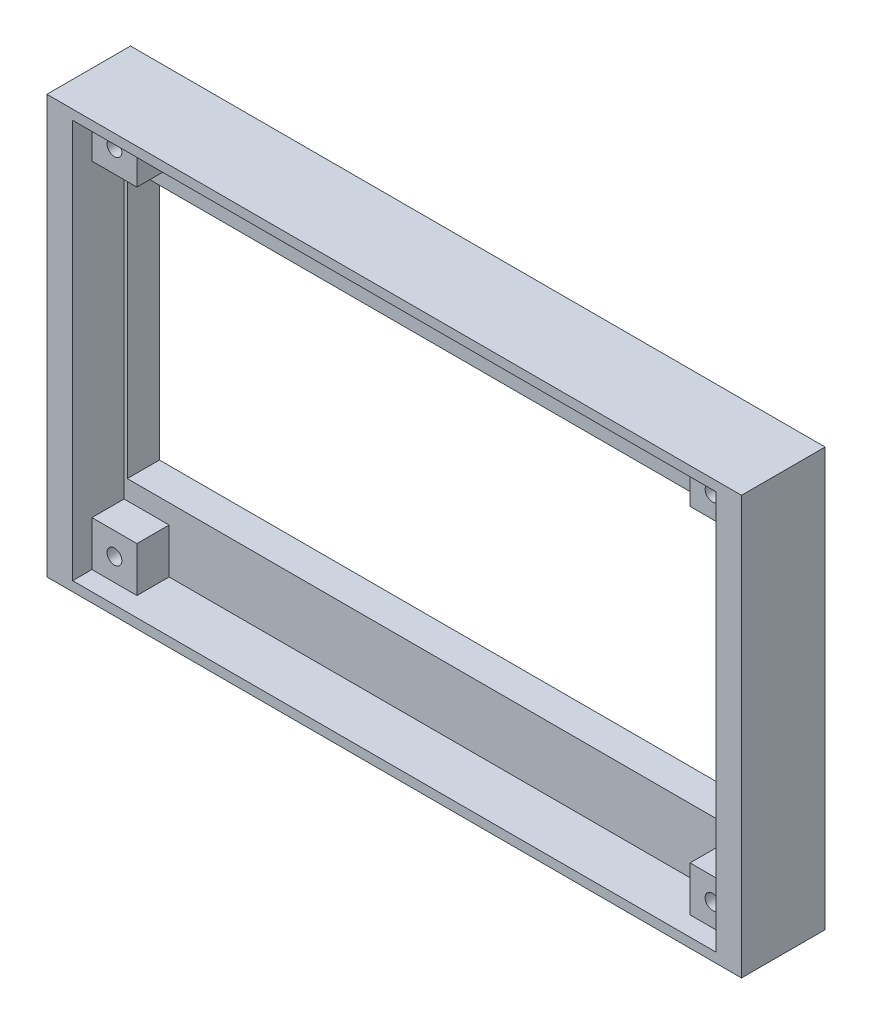
SolidWorks part; units mm, degrees
material "ABS"
ref_plane "前基準面" through (0, 0, 0) normal (0, 0, 1) x (1, 0, 0)
ref_plane "上基準面" through (0, 0, 0) normal (0, 1, 0) x (1, 0, 0)
ref_plane "右基準面" through (0, 0, 0) normal (1, 0, 0) x (0, 0, -1)
sketch "草圖1" plane through (0, 0, 0) normal (0, 0, 1) x (1, 0, 0)
  line L1 (-43.4248, 26.0298) -> (64.5752, 26.0298)
  line L2 (-43.4248, 26.0298) -> (-43.4248, -38.9702)
  line L3 (-43.4248, -38.9702) -> (64.5752, -38.9702)
  line L4 (64.5752, 26.0298) -> (64.5752, -38.9702)
  line L5 (-38.9248, 14.5298) -> (60.0752, 14.5298)
  line L6 (-38.9248, 14.5298) -> (-38.9248, -27.4702)
  line L7 (-38.9248, -27.4702) -> (60.0752, -27.4702)
  line L8 (60.0752, 14.5298) -> (60.0752, -27.4702)
  dimension "D1" = 108
  dimension "D2" = 65
  dimension "D3" = 42
  dimension "D4" = 99
  dimension "D5" = 4.5
  dimension "D6" = 11.5
extrude "填料-伸長1" add sketch "草圖1" along normal blind 5
sketch "草圖2" plane through (0, 0, 5) normal (0, 0, 1) x (1, 0, 0)
  line L0 (64.5752, 26.0298) -> (-43.4248, 26.0298) construction
  line L1 (-39.4248, 24.5298) -> (60.5752, 24.5298)
  line L2 (-39.4248, 24.5298) -> (-39.4248, -37.4702)
  line L3 (-39.4248, -37.4702) -> (60.5752, -37.4702)
  line L4 (60.5752, 24.5298) -> (60.5752, -37.4702)
  line L5 (-43.4248, 26.0298) -> (-43.4248, -38.9702) construction
  line L7 (-39.4248, 24.5298) -> (-32.4248, 24.5298)
  line L8 (-39.4248, 24.5298) -> (-39.4248, 17.5298)
  line L9 (-39.4248, 17.5298) -> (-32.4248, 17.5298)
  line L10 (-32.4248, 24.5298) -> (-32.4248, 17.5298)
  line L11 (60.5752, 24.5298) -> (53.5752, 24.5298)
  line L12 (60.5752, 24.5298) -> (60.5752, 17.5298)
  line L13 (60.5752, 17.5298) -> (53.5752, 17.5298)
  line L14 (53.5752, 24.5298) -> (53.5752, 17.5298)
  line L15 (-39.4248, -37.4702) -> (-32.4248, -37.4702)
  line L16 (-39.4248, -37.4702) -> (-39.4248, -30.4702)
  line L17 (-39.4248, -30.4702) -> (-32.4248, -30.4702)
  line L18 (-32.4248, -37.4702) -> (-32.4248, -30.4702)
  line L19 (60.5752, -37.4702) -> (53.5752, -37.4702)
  line L20 (60.5752, -37.4702) -> (60.5752, -30.4702)
  line L21 (60.5752, -30.4702) -> (53.5752, -30.4702)
  line L22 (53.5752, -37.4702) -> (53.5752, -30.4702)
  line M3 (-43.4248, 26.0298) -> (-43.4248, -38.9702)
  line M4 (-43.4248, -38.9702) -> (64.5752, -38.9702)
  line M5 (64.5752, -38.9702) -> (64.5752, 26.0298)
  line M6 (64.5752, 26.0298) -> (-43.4248, 26.0298)
  dimension "D1" = 100
  dimension "D2" = 62
  dimension "D3" = 1.5
  dimension "D4" = 4
  dimension "D5" = 7
  dimension "7" = 7
  dimension "D6" = 7
  dimension "D7" = 7
  dimension "D8" = 7
  dimension "D9" = 7
  dimension "D10" = 7
  dimension "D11" = 7
extrude "填料-伸長2" add sketch "草圖2" along normal blind 5 contours L1 L4 L3 L2 M6 M3 M4 M5 | L10 L1 L2 L9 | L1 L14 L13 L4 | L22 L3 L4 L21 | L3 L18 L17 L2
sketch "草圖3" plane through (0, 0, 10) normal (0, 0, 1) x (1, 0, 0)
  line L1 (-32.4248, 24.5298) -> (-39.4248, 24.5298)
  line L2 (-32.4248, 24.5298) -> (-32.4248, 17.5298)
  line L3 (-32.4248, 17.5298) -> (-39.4248, 17.5298)
  line L4 (-39.4248, 24.5298) -> (-39.4248, 17.5298)
  line L5 (60.5752, 17.5298) -> (53.5752, 17.5298)
  line L6 (60.5752, 17.5298) -> (60.5752, 24.5298)
  line L7 (60.5752, 24.5298) -> (53.5752, 24.5298)
  line L8 (53.5752, 17.5298) -> (53.5752, 24.5298)
  line L9 (60.5752, -30.4702) -> (53.5752, -30.4702)
  line L10 (60.5752, -30.4702) -> (60.5752, -37.4702)
  line L11 (60.5752, -37.4702) -> (53.5752, -37.4702)
  line L12 (53.5752, -30.4702) -> (53.5752, -37.4702)
  line L13 (-39.4248, -30.4702) -> (-32.4248, -30.4702)
  line L14 (-39.4248, -30.4702) -> (-39.4248, -37.4702)
  line L15 (-39.4248, -37.4702) -> (-32.4248, -37.4702)
  line L16 (-32.4248, -30.4702) -> (-32.4248, -37.4702)
  line L17 (-39.4248, -37.4702) -> (60.5752, -37.4702)
  line L18 (-39.4248, -37.4702) -> (-39.4248, 24.5298)
  line L19 (-39.4248, 24.5298) -> (60.5752, 24.5298)
  line L20 (60.5752, -37.4702) -> (60.5752, 24.5298)
  line M3 (-32.4248, 24.5298) -> (53.5752, 24.5298)
  line M6 (60.5752, 17.5298) -> (60.5752, -30.4702)
  line M9 (53.5752, -37.4702) -> (-32.4248, -37.4702)
  line M12 (-39.4248, -30.4702) -> (-39.4248, 17.5298)
  line M14 (64.5752, 26.0298) -> (-43.4248, 26.0298)
  line M15 (-43.4248, 26.0298) -> (-43.4248, -38.9702)
  line M16 (-43.4248, -38.9702) -> (64.5752, -38.9702)
  line M17 (64.5752, -38.9702) -> (64.5752, 26.0298)
extrude "填料-伸長4" add sketch "草圖3" along normal blind 3 contours L15 L14 L4 L1 L7 L6 L10 L11 M17 M14 M15 M16 M12 M3 M6 M9
sketch "草圖4" plane through (0, 0, 10) normal (0, 0, 1) x (1, 0, 0)
  line L0 (-32.4248, 24.5298) -> (-39.4248, 24.5298) construction
  line L1 (-39.4248, 24.5298) -> (-39.4248, 17.5298) construction
  line L2 (60.5752, 24.5298) -> (53.5752, 24.5298) construction
  line L3 (60.5752, 17.5298) -> (60.5752, 24.5298) construction
  line L4 (60.5752, -37.4702) -> (60.5752, -30.4702) construction
  line L5 (53.5752, -37.4702) -> (60.5752, -37.4702) construction
  line L6 (-39.4248, -30.4702) -> (-39.4248, -37.4702) construction
  line L7 (-39.4248, -37.4702) -> (-32.4248, -37.4702) construction
  circle A0 centre (-35.9248, 21.0298) radius 1.15
  circle A1 centre (57.0752, 21.0298) radius 1.15
  circle A2 centre (57.0752, -33.9702) radius 1.15
  circle A3 centre (-35.9248, -33.9702) radius 1.15
  dimension "D1" = 3.5
  dimension "D2" = 3.5
  dimension "D3" = 2.3
  dimension "D4" = 2.3
  dimension "D5" = 3.5
  dimension "D6" = 3.5
  dimension "D7" = 3.5
  dimension "D8" = 2.3
  dimension "D9" = 3.5
  dimension "D10" = 2.3
  dimension "D11" = 3.5
  dimension "D12" = 3.5
extrude "除料-伸長1" cut sketch "草圖4" against normal blind 7
